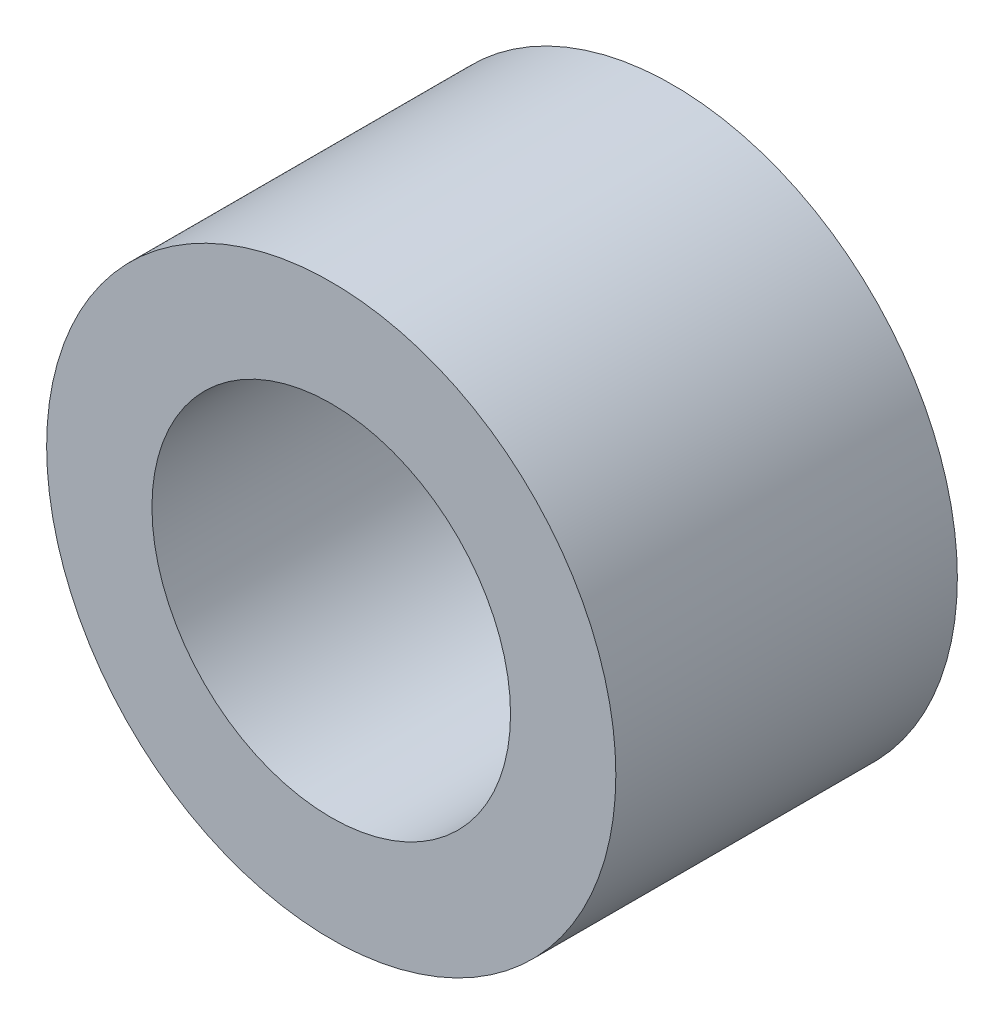
SolidWorks part; units mm, degrees
ref_plane "Front Plane" through (0, 0, 0) normal (0, 0, 1) x (1, 0, 0)
ref_plane "Top Plane" through (0, 0, 0) normal (0, 1, 0) x (1, 0, 0)
ref_plane "Right Plane" through (0, 0, 0) normal (1, 0, 0) x (0, 0, -1)
sketch "Sketch1" plane through (0, 0, 0) normal (0, 0, 1) x (1, 0, 0)
  circle A0 centre (0, 0) radius 5
  circle A1 centre (0, 0) radius 3.15
  dimension "OD" = 10
  dimension "ID" = 6.3
extrude "Extrude1" add sketch "Sketch1" along normal mid plane 6
sketch "Sketch2" plane through (0, 0, 0) normal (1, 0, 0) x (0, 0, -1)
  line L0 (-3, -3.15) -> (3, -3.15) construction
  line L3 (3, 3.15) -> (-3, 3.15) construction
  line L5 (-3, -3.15) -> (3, -3.15)
  line L6 (3, 3.15) -> (-3, 3.15)
sketch "Sketch4" plane through (0, 0, 3) normal (0, 0, 1) x (1, 0, 0)
  line L0 (0, 0) -> (-2.2274, 2.2274)
  line L1 (0, -55) -> (0, 55) construction
  circle A0 centre (0, 0) radius 3.15 construction
  dimension "D1" = 45
